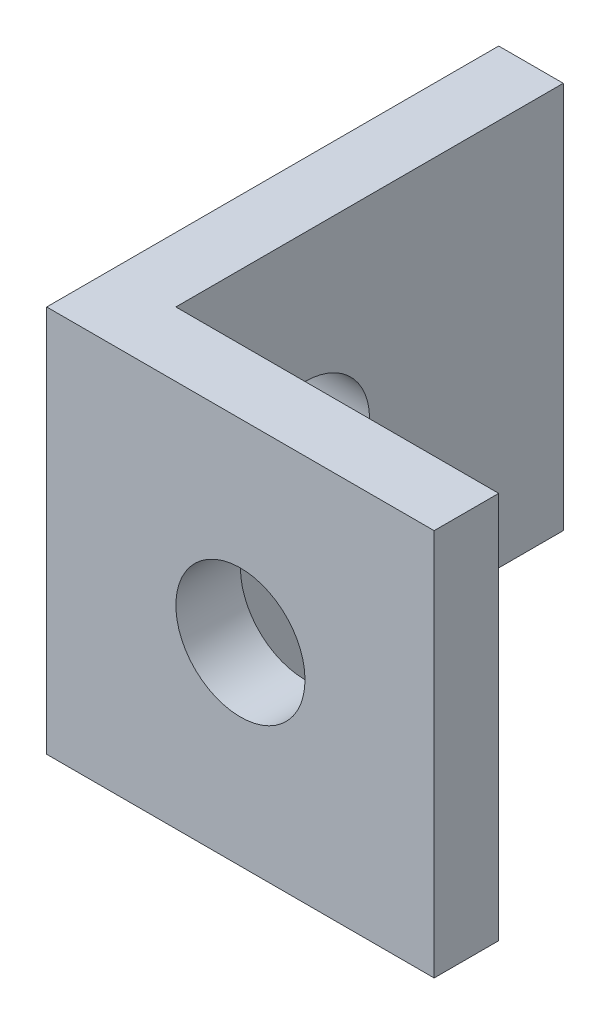
SolidWorks part; units mm, degrees
ref_plane "Alzado" through (0, 0, 0) normal (0, 0, 1) x (1, 0, 0)
ref_plane "Planta" through (0, 0, 0) normal (0, 1, 0) x (1, 0, 0)
ref_plane "Vista lateral" through (0, 0, 0) normal (1, 0, 0) x (0, 0, -1)
sketch "Croquis1" plane through (0, 0, 0) normal (0, 1, 0) x (1, 0, 0)
  line L1 (-15, -2.5) -> (15, -2.5)
  line L2 (-15, -2.5) -> (-15, 2.5)
  line L3 (-15, 2.5) -> (15, 2.5)
  line L4 (15, -2.5) -> (15, 2.5)
  line L5 (-15, -2.5) -> (15, 2.5) construction
  line L6 (-15, 2.5) -> (15, -2.5) construction
  line L7 (-10, 32.5) -> (-15, 32.5)
  line L8 (-10, 32.5) -> (-10, 2.5)
  line L9 (-10, 2.5) -> (-15, 2.5)
  line L10 (-15, 32.5) -> (-15, 2.5)
  line L11 (-10, 32.5) -> (-15, 2.5) construction
  line L12 (-10, 2.5) -> (-15, 32.5) construction
  point P0 (0, 0)
  point P6 (-12.5, 17.5)
  dimension "D1" = 30
  dimension "D2" = 5
  dimension "D3" = 30
  dimension "D4" = 5
extrude "Saliente-Extruir1" add sketch "Croquis1" along normal blind 30 contours L7 L10 L3 L8 | L1 L4 L3 L2
sketch "Croquis2" plane through (0, 0, 2.5) normal (0, 0, 1) x (1, 0, 0)
  line L0 (-15, 30) -> (-15, 0) construction
  line L1 (-15, 0) -> (15, 0) construction
  circle A0 centre (0, 15) radius 5
  dimension "D1" = 15
  dimension "D2" = 15
extrude "Cortar-Extruir1" cut sketch "Croquis2" against normal up to surface (5 mm away) up to face at (2.5, 15, -2.5)
sketch "Croquis3" plane through (-15, 0, 0) normal (-1, 0, 0) x (0, 0, 1)
  line L0 (2.5, 30) -> (2.5, 0) construction
  line L1 (-32.5, 0) -> (2.5, 0) construction
  circle A0 centre (-12.5, 15) radius 5
  dimension "D1" = 15
  dimension "D2" = 15
extrude "Cortar-Extruir2" cut sketch "Croquis3" against normal up to surface (5 mm away) up to face at (-10, 15, -17.5)
